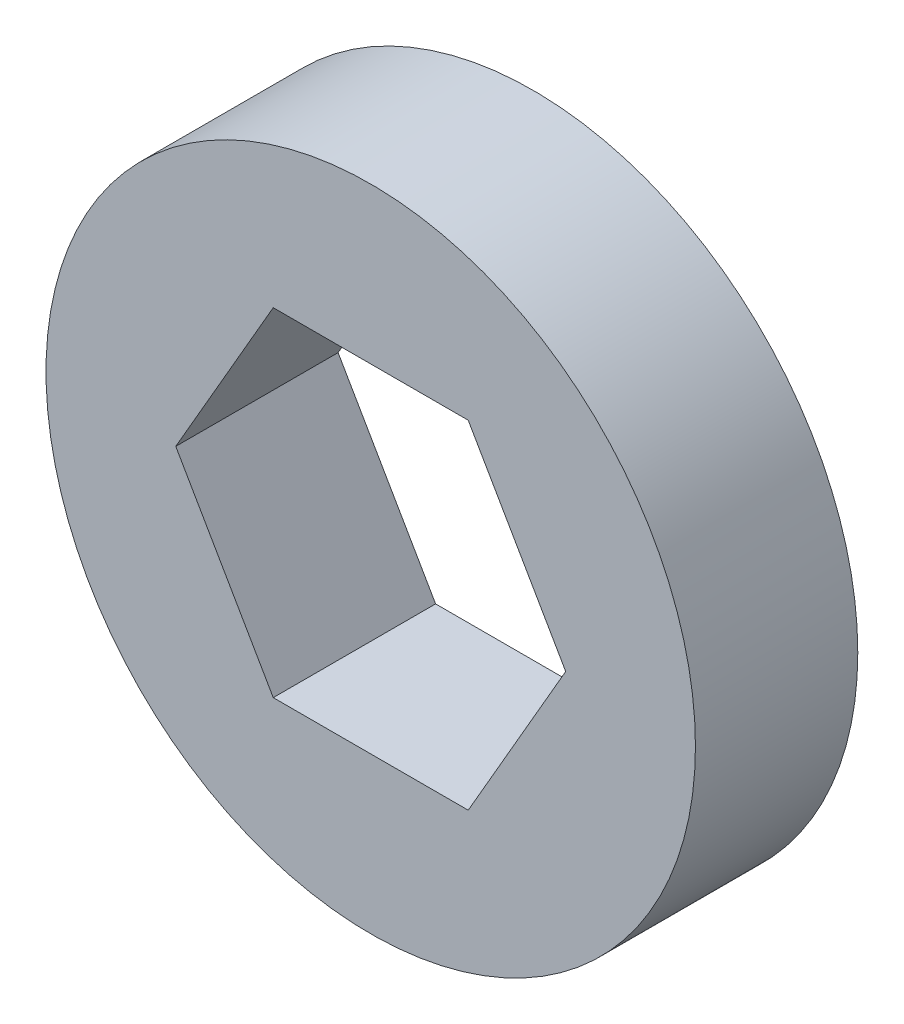
SolidWorks part; units mm, degrees
ref_plane "Front Plane" through (0, 0, 0) normal (0, 0, 1) x (1, 0, 0)
ref_plane "Top Plane" through (0, 0, 0) normal (0, 1, 0) x (1, 0, 0)
ref_plane "Right Plane" through (0, 0, 0) normal (1, 0, 0) x (0, 0, -1)
sketch "Sketch1" plane through (0, 0, 0) normal (0, 0, 1) x (1, 0, 0)
  line L1 (3.8128, -6.604) -> (7.6256, 0)
  line L2 (7.6256, 0) -> (3.8128, 6.604)
  line L3 (3.8128, 6.604) -> (-3.8128, 6.604)
  line L4 (-3.8128, 6.604) -> (-7.6256, 0)
  line L5 (-7.6256, 0) -> (-3.8128, -6.604)
  line L6 (-3.8128, -6.604) -> (3.8128, -6.604)
  circle A0 centre (0, 0) radius 6.604 construction
  circle A1 centre (0, 0) radius 12.7
  dimension "D2" = 25.4
  dimension "D1" = 13.208
extrude "Boss-Extrude1" add sketch "Sketch1" along normal blind 6.35
